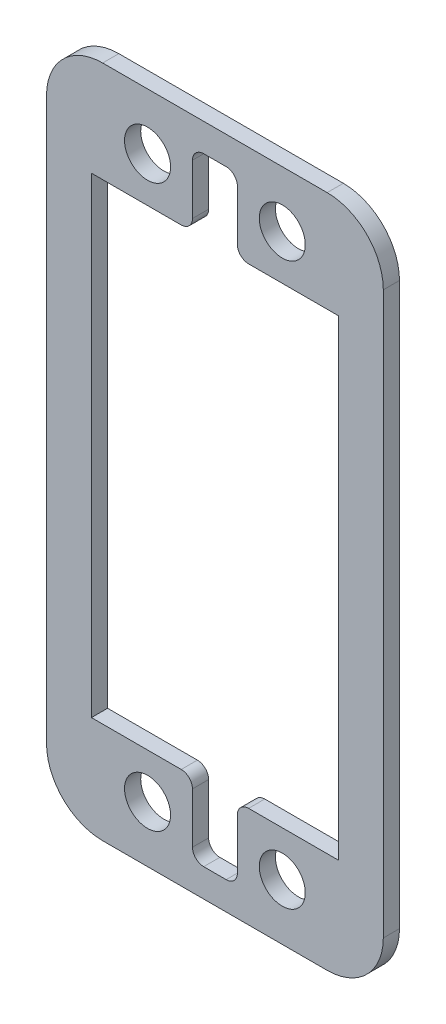
SolidWorks part; units mm, degrees
ref_plane "Alzado" through (0, 0, 0) normal (0, 0, 1) x (1, 0, 0)
ref_plane "Planta" through (0, 0, 0) normal (0, 1, 0) x (1, 0, 0)
ref_plane "Vista lateral" through (0, 0, 0) normal (1, 0, 0) x (0, 0, -1)
sketch "Croquis1" plane through (0, 0, 0) normal (0, 0, 1) x (1, 0, 0)
  line L0 (-15, 30) -> (15, 30)
  line L1 (15, 30) -> (15, -30)
  line L2 (15, -30) -> (-15, -30)
  line L3 (-15, -30) -> (-15, 30)
  line L4 (0, 0) -> (3.1755, 0) construction
  line L5 (0, 0) -> (0, 1.2752) construction
  dimension "D1" = 60
  dimension "D2" = 30
extrude "Saliente-Extruir1" add sketch "Croquis1" along normal blind 1.44
sketch "Croquis2" plane through (0, 0, 0) normal (0, 0, -1) x (-1, 0, 0)
  line L0 (-11, 21) -> (11, 21)
  line L1 (11, 21) -> (11, -21)
  line L2 (11, -21) -> (-11, -21)
  line L3 (-11, -21) -> (-11, 21)
  line L4 (0, 0) -> (17.9824, 0) construction
  line L5 (0, 0) -> (0, 11.2002) construction
  dimension "D1" = 22
  dimension "D2" = 42
extrude "Cortar-Extruir1" cut sketch "Croquis2" against normal through all
sketch "Croquis3" plane through (0, 0, 0) normal (0, 0, -1) x (-1, 0, 0)
  line L0 (0, 0) -> (-26.2125, 0) construction
  line L1 (0, 0) -> (0, 9.0898) construction
  line L2 (-2, 21) -> (-2, 27.5)
  line L3 (11, 21) -> (-11, 21) construction
  line L4 (-2, 27.5) -> (2, 27.5)
  line L5 (2, 27.5) -> (2, -27.5)
  line L6 (2, -27.5) -> (-2, -27.5)
  line L7 (-2, -27.5) -> (-2, 21)
  circle A0 centre (-6, 25) radius 2.05
  circle A1 centre (6, 25) radius 2.05
  circle A2 centre (-6, -25) radius 2.05
  circle A3 centre (6, -25) radius 2.05
  dimension "D1" = 4.1
  dimension "D2" = 4.1
  dimension "D3" = 4.1
  dimension "D4" = 4.1
  dimension "D5" = 12
  dimension "D6" = 12
  dimension "D7" = 50
  dimension "D8" = 25
  dimension "D9" = 4
  dimension "D10" = 55
extrude "Cortar-Extruir2" cut sketch "Croquis3" against normal through all
fillet "Redondeo1" radius 5 4 edges at (-15, -30, 0.72) (15, -30, 0.72) (15, 30, 0.72) (-15, 30, 0.72)
fillet "Redondeo3" radius 1 8 edges at (-2, -27.5, 0.72) (-2, -21, 0.72) (2, -21, 0.72) (2, -27.5, 0.72) (2, 27.5, 0.72) (-2, 27.5, 0.72) (2, 21, 0.72) (-2, 21, 0.72)
